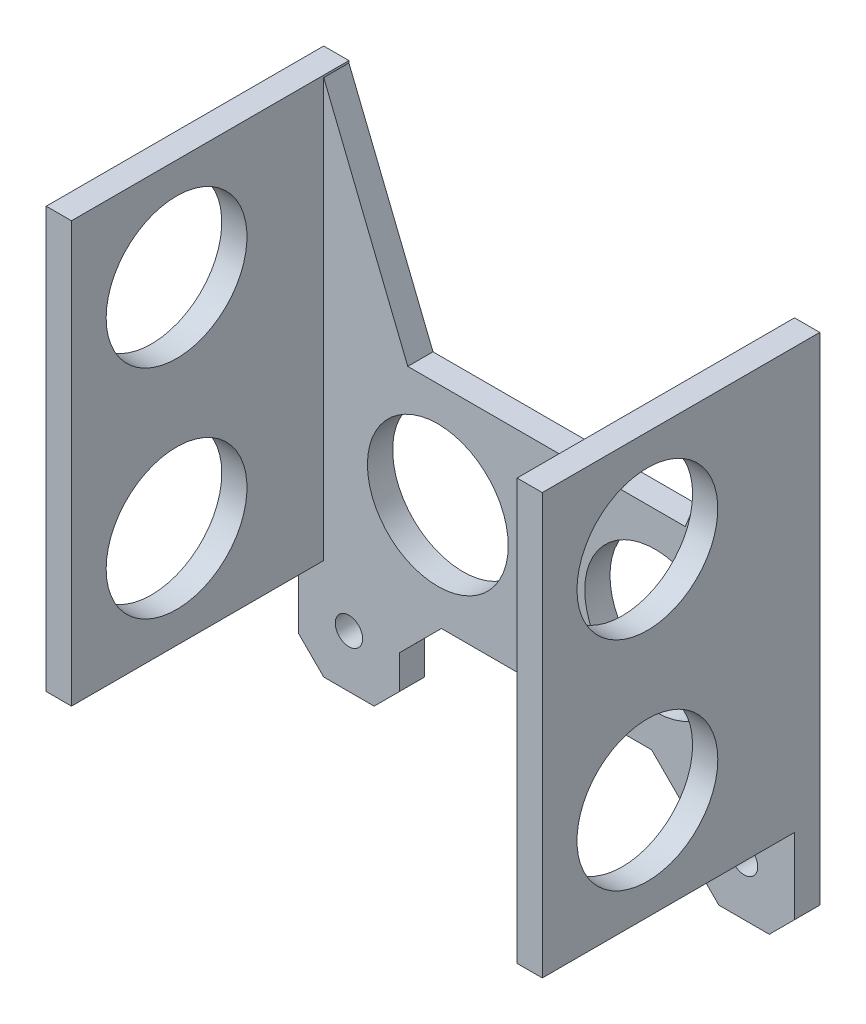
SolidWorks part; units mm, degrees
ref_plane "Alzado" through (0, 0, 0) normal (0, 0, 1) x (1, 0, 0)
ref_plane "Planta" through (0, 0, 0) normal (0, 1, 0) x (1, 0, 0)
ref_plane "Vista lateral" through (0, 0, 0) normal (1, 0, 0) x (0, 0, -1)
sketch "Croquis1" plane through (0, 0, 0) normal (0, 1, 0) x (1, 0, 0)
  line L0 (-26.5, 0) -> (-26.5, -30)
  line L1 (-26.5, -30) -> (-29.5, -30)
  line L2 (-29.5, -30) -> (-29.5, 3)
  line L3 (-29.5, 3) -> (29.5, 3)
  line L4 (-26.5, 0) -> (26.5, 0)
  line L5 (0, 5.3559) -> (0, -41.232) construction
  line L6 (29.5, -30) -> (29.5, 3)
  line L7 (26.5, -30) -> (29.5, -30)
  line L8 (26.5, 0) -> (26.5, -30)
  point P10 (0, 0)
  point P11 (0, 3)
  dimension "D1" = 29.5
  dimension "D2" = 30
  dimension "D3" = 3
  dimension "D4" = 3
extrude "Saliente-Extruir1" add sketch "Croquis1" along normal blind 25
sketch "Croquis2" plane through (0, 0, 0) normal (0, 0, 1) x (1, 0, 0)
  line L0 (0, 0) -> (0, 34.0617) construction
  line L1 (-26.5, 0) -> (26.5, 0) construction
  circle A0 centre (-12.925, 12.5) radius 8.375
  circle A1 centre (12.925, 12.5) radius 8.375
  dimension "D1" = 16.75
  dimension "D3" = 12.5
  dimension "D2" = 12.925
extrude "Cortar-Extruir1" cut sketch "Croquis2" against normal through all both and the other way through all
sketch "Croquis3" plane through (26.5, 0, 0) normal (-1, 0, 0) x (0, 0, 1)
  line L0 (-3, 0) -> (30, 0) construction
  line L1 (0, 25) -> (30, 25)
  line L3 (0, 50) -> (30, 50)
  line L4 (30, 25) -> (30, 50)
  line L5 (-3, 25) -> (-3, 50)
  line L6 (-3, 50) -> (0, 50)
  line L7 (-3, 25) -> (0, 25)
  line L8 (30, 25) -> (30, 0) construction
  dimension "D1" = 50
extrude "Saliente-Extruir2" add sketch "Croquis3" against normal up to vertex (3 mm away) up to point (29.5, 25, 30)
sketch "Croquis4" plane through (-29.5, 0, 0) normal (-1, 0, 0) x (0, 0, 1)
  line L0 (30, 50) -> (30, 0) construction
  line L1 (0, 25) -> (30, 25)
  line L3 (0, 50) -> (30, 50)
  line L4 (30, 25) -> (30, 50)
  line L5 (0, 50) -> (-3, 50)
  line L6 (-3, 50) -> (-3, 25)
  line L7 (-3, 25) -> (0, 25)
extrude "Saliente-Extruir3" add sketch "Croquis4" against normal up to vertex (3 mm away) up to point (-26.5, 25, 30)
sketch "Croquis5" plane through (-29.5, 0, 0) normal (-1, 0, 0) x (0, 0, 1)
  line L0 (0, 25) -> (0, 0) construction
  line L2 (12.5, 5.9782) -> (30, 25) construction
  line L3 (30, 50) -> (30, 0) construction
  line L4 (25, 25) -> (5.9893, 25) construction
  circle A0 centre (17.5, 37.925) radius 8.375
  circle A1 centre (17.5, 12.075) radius 8.375
  dimension "D1" = 16.75
  dimension "D2" = 12.925
  dimension "D3" = 17.5
extrude "Cortar-Extruir2" cut sketch "Croquis5" against normal through all
chamfer "Chaflán1" distance 10 angle 68 2 edges at (-26.5, 25, -1.5) (26.5, 25, -1.5)
sketch "Croquis6" plane through (0, 0, 0) normal (0, 0, 1) x (1, 0, 0)
  line L0 (0, 0) -> (0, -11.3922) construction
  line L1 (-29.5, 0) -> (-17.5, 0)
  line L2 (-29.5, 0) -> (-29.5, -12)
  line L3 (-29.5, -12) -> (-17.5, -12)
  line L11 (-12.5, 0) -> (-17.5, 0)
  line L12 (12.5, 0) -> (17.5, 0)
  line L14 (29.5, -12) -> (17.5, -12)
  line L15 (29.5, 0) -> (29.5, -12)
  line L16 (29.5, 0) -> (17.5, 0)
  line L17 (-17.5, -12) -> (-17.5, -5.002)
  line L18 (-17.5, -5.002) -> (-12.5, 0)
  line L19 (17.5, -12) -> (17.5, -5.002)
  line L20 (17.5, -5.002) -> (12.5, 0)
  circle A0 centre (-23.5, -5.75) radius 1.625
  circle A2 centre (23.5, -5.75) radius 1.625
  dimension "D3" = 3.25
  dimension "D1" = 12
  dimension "D2" = 12
  dimension "D4" = 5.75
  dimension "D5" = 6
  dimension "D6" = 5.002
  dimension "D7" = 5
extrude "Saliente-Extruir4" add sketch "Croquis6" against normal blind 3
chamfer "Chaflán2" distance 3 angle 45 4 edges at (29.5, -12, -1.5) (17.5, -12, -1.5) (-17.5, -12, -1.5) (-29.5, -12, -1.5)
